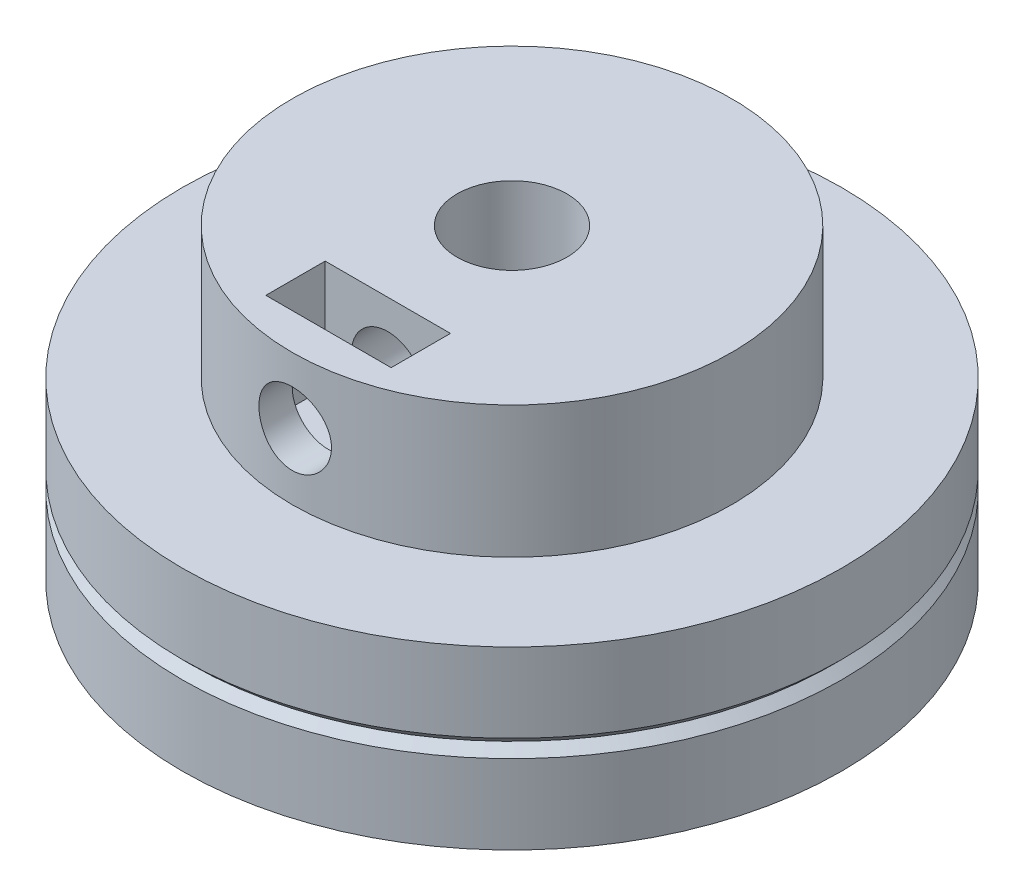
SolidWorks part; units mm, degrees
ref_plane "Front Plane" through (0, 0, 0) normal (0, 0, 1) x (1, 0, 0)
ref_plane "Top Plane" through (0, 0, 0) normal (0, 1, 0) x (1, 0, 0)
ref_plane "Right Plane" through (0, 0, 0) normal (1, 0, 0) x (0, 0, -1)
sketch "Sketch1" plane through (0, 0, 0) normal (0, 0, 1) x (1, 0, 0)
  line L0 (0, 0) -> (0, 13.3528) construction
  line L1 (2.5, 8) -> (15, 8)
  line L2 (15, 8) -> (15, 4.4)
  line L3 (15, 4.4) -> (14.6, 4)
  line L4 (14.6, 4) -> (15, 3.6)
  line L5 (15, 3.6) -> (15, 0)
  line L6 (15, 0) -> (2.5, 0)
  line L7 (14.6, 4) -> (14.6, 0) construction
  line L8 (14.6, 4) -> (14.6, 8) construction
  line L9 (2.5, 8) -> (2.5, 0)
  dimension "D1" = 30
  dimension "D2" = 5
  dimension "D3" = 0.4
  dimension "D4" = 8
revolve "Revolve1" add sketch "Sketch1" angle 360 about L0
sketch "Sketch2" plane through (0, 8, 0) normal (0, 1, 0) x (1, 0, 0)
  circle A0 centre (0, 0) radius 2.5
  circle A1 centre (0, 0) radius 10
  dimension "D1" = 20
extrude "Boss-Extrude1" add sketch "Sketch2" along normal blind 6
sketch "Sketch3" plane through (0, 14, 0) normal (0, 1, 0) x (1, 0, 0)
  line L0 (0, 0) -> (0, -13.3796) construction
  line L2 (-2.85, -8.35) -> (2.85, -8.35)
  line L3 (-2.85, -8.35) -> (-2.85, -5.65)
  line L4 (-2.85, -5.65) -> (2.85, -5.65)
  line L5 (2.85, -8.35) -> (2.85, -5.65)
  line L6 (-2.85, -8.35) -> (2.85, -5.65) construction
  line L7 (-2.85, -5.65) -> (2.85, -8.35) construction
  point P3 (0, -7)
  dimension "D1" = 2.7
  dimension "D2" = 5.7
  dimension "D3" = 7
extrude "Cut-Extrude1" cut sketch "Sketch3" against normal blind 5
sketch "Sketch4" plane through (0, 0, 0) normal (0, 0, 1) x (1, 0, 0)
  line L0 (10, 14) -> (-10, 14) construction
  circle A0 centre (0, 11) radius 1.65
  point P4 (0, 0)
  dimension "D1" = 3.3
  dimension "D2" = 3
extrude "Cut-Extrude2" cut sketch "Sketch4" along normal blind 35
